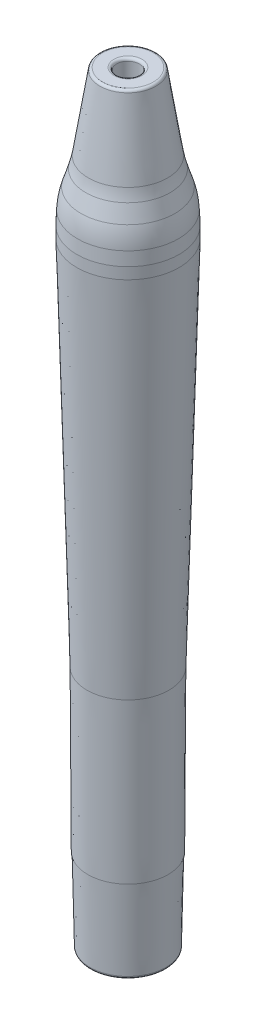
SolidWorks part; units mm, degrees
ref_plane "前视基准面" through (0, 0, 0) normal (0, 0, 1) x (1, 0, 0)
ref_plane "上视基准面" through (0, 0, 0) normal (0, 1, 0) x (1, 0, 0)
ref_plane "右视基准面" through (0, 0, 0) normal (1, 0, 0) x (0, 0, -1)
sketch "草图1" plane through (0, 0, 0) normal (0, 0, 1) x (1, 0, 0)
  line L0 (14.1873, 38.6453) -> (23.6273, 38.6453)
  line L1 (23.6273, 38.6453) -> (21.7573, -29.9092)
  line L2 (21.7573, -29.9092) -> (14.1873, -29.9092)
  line L3 (14.1873, -29.9092) -> (14.1873, 38.6453)
  dimension "D1" = 68.58
  dimension "D2" = 9.44
  dimension "D3" = 7.57
revolve "旋转1" add sketch "草图1" angle 360 about L3
sketch "草图3" plane through (0, 0, 0) normal (0, 0, 1) x (1, 0, 0)
  line L0 (14.1873, 38.6453) -> (23.6273, 38.6453)
  line L1 (23.6273, 38.6453) -> (4.7473, 38.6453) construction
  line L2 (23.6273, 38.6453) -> (23.6273, 40.7453)
  line L3 (23.6273, 40.7453) -> (14.1873, 40.7453)
  line L4 (14.1873, 40.7453) -> (14.1873, 38.6453)
  dimension "D1" = 2.1
revolve "旋转2" add sketch "草图3" angle 360 about L4
sketch "草图5" plane through (0, 0, 0) normal (0, 0, 1) x (1, 0, 0)
  line L0 (14.1873, 40.7453) -> (23.6273, 40.7453)
  line L1 (23.6273, 40.7453) -> (4.7473, 40.7453) construction
  line L3 (19.2973, 65.9653) -> (16.2873, 65.9653)
  line L4 (14.1873, 60.4653) -> (14.1873, 40.7453)
  line L5 (19.2973, 65.9653) -> (21.4861, 51.9145)
  line L6 (21.9732, 49.8037) -> (22.8635, 46.9163)
  line L7 (23.5131, 43.1953) -> (23.6273, 40.7453)
  line L8 (16.2873, 65.9653) -> (16.2873, 60.4653)
  line L9 (16.2873, 60.4653) -> (14.1873, 60.4653)
  arc A0 (21.4861, 51.9145) -> (21.9732, 49.8037) centre (36.3074, 54.2233) ccw
  arc A1 (22.8635, 46.9163) -> (23.5131, 43.1953) centre (8.5294, 42.4967) cw
  dimension "D3" = 15
  dimension "D1" = 25.22
  dimension "D4" = 5.5
  dimension "D5" = 2.1
revolve "旋转3" add sketch "草图5" angle 360 about L4
sketch "草图6" plane through (0, 0, 0) normal (0, 0, 1) x (1, 0, 0)
  line L0 (14.1873, -29.9092) -> (21.7573, -29.9092)
  line L1 (6.6173, -29.9092) -> (21.7573, -29.9092) construction
  line L2 (21.7573, -29.9092) -> (21.6073, -59.4788)
  line L3 (21.6073, -59.4788) -> (21.4973, -59.4788)
  line L4 (14.1873, -59.4788) -> (14.1873, -29.9092)
  line L5 (21.4973, -59.4788) -> (21.1773, -75.027)
  line L6 (21.1773, -75.027) -> (14.1873, -75.027)
  line L7 (14.1873, -75.027) -> (14.1873, -59.4788)
  dimension "D1" = 29.57
  dimension "D2" = 7.42
  dimension "D3" = 6.99
  dimension "D4" = 7.31
revolve "旋转4" add sketch "草图6" angle 360 about L4
fillet "圆角1" radius 0.5 3 edges at (12.0873, 65.9653, 0) (9.0773, 65.9653, 0) (14.1873, -75.027, -6.99)
